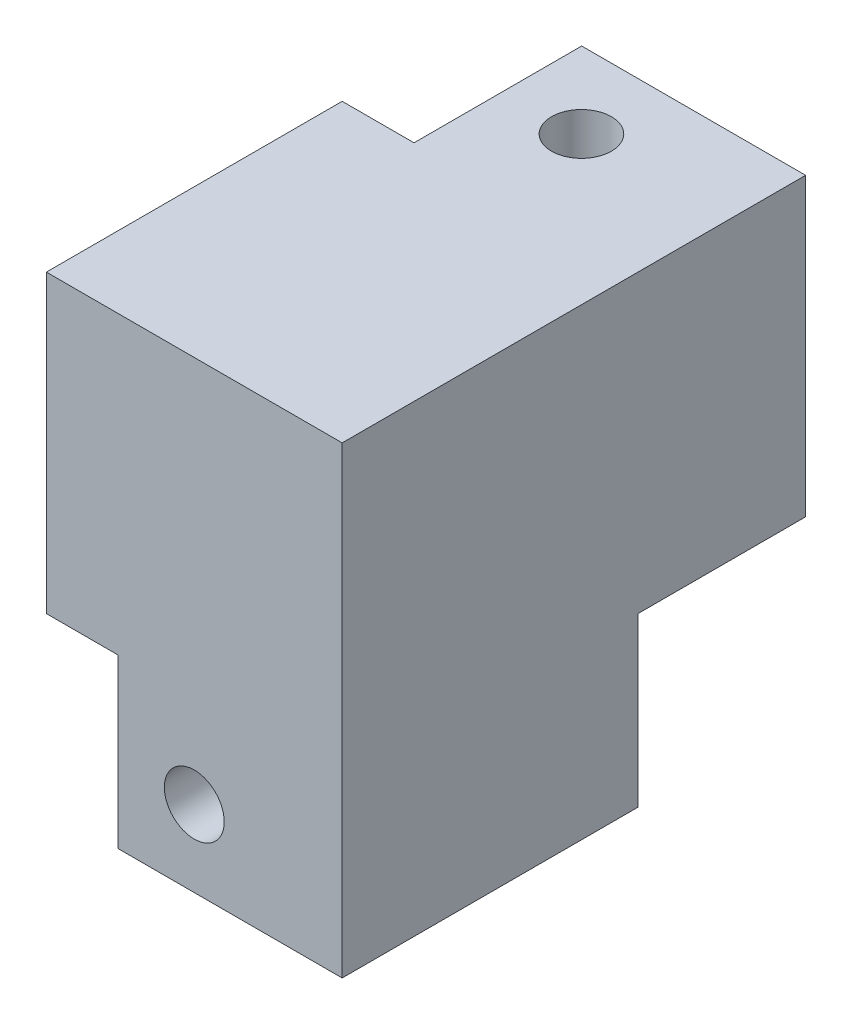
SolidWorks part; units mm, degrees
ref_plane "前视基准面" through (0, 0, 0) normal (0, 0, 1) x (1, 0, 0)
ref_plane "上视基准面" through (0, 0, 0) normal (0, 1, 0) x (1, 0, 0)
ref_plane "右视基准面" through (0, 0, 0) normal (1, 0, 0) x (0, 0, -1)
sketch "草图1" plane through (0, 0, 0) normal (0, 1, 0) x (1, 0, 0)
  line L1 (-6.35, -6.35) -> (6.35, -6.35)
  line L2 (-6.35, -6.35) -> (-6.35, 6.35)
  line L3 (-6.35, 6.35) -> (6.35, 6.35)
  line L4 (6.35, -6.35) -> (6.35, 6.35)
  line L5 (-6.35, -6.35) -> (6.35, 6.35) construction
  line L6 (-6.35, 6.35) -> (6.35, -6.35) construction
  line L7 (12.35, -12.35) -> (-12.35, -12.35)
  line L8 (12.35, -12.35) -> (12.35, 12.35)
  line L9 (12.35, 12.35) -> (-12.35, 12.35)
  line L10 (-12.35, -12.35) -> (-12.35, 12.35)
  line L11 (12.35, -12.35) -> (-12.35, 12.35) construction
  line L12 (12.35, 12.35) -> (-12.35, -12.35) construction
  point P0 (0, 0)
  point P6 (0, 0)
  dimension "D1" = 12.7
  dimension "D2" = 12.7
  dimension "D3" = 6
  dimension "D4" = 6
extrude "凸台-拉伸2" add sketch "草图1" along normal blind 24.7 contours L1 L4 L3 L2 | L10 L7 L8 L9 L4 L1 L2 L3
sketch "草图3" plane through (0, 0, 0) normal (0, -1, 0) x (1, 0, 0)
  line L0 (-6.35, 6.35) -> (-6.35, 12.35)
  line L1 (-6.35, -6.35) -> (6.35, -6.35)
  line L2 (-6.35, -6.35) -> (-6.35, 6.35)
  line L3 (-6.35, 6.35) -> (6.35, 6.35)
  line L4 (6.35, -6.35) -> (6.35, 6.35)
  line L5 (-6.35, -6.35) -> (6.35, 6.35) construction
  line L6 (-6.35, 6.35) -> (6.35, -6.35) construction
  line L7 (12.35, 12.35) -> (-12.35, 12.35) construction
  line L8 (-6.35, 12.35) -> (12.35, 12.35)
  line L9 (12.35, 12.35) -> (12.35, -12.35)
  line L10 (12.35, -12.35) -> (-6.35, -12.35)
  line L11 (12.35, -12.35) -> (-12.35, -12.35) construction
  line L12 (-6.35, -12.35) -> (-6.35, -6.35)
  point P0 (0, 0)
  line M4 (-12.35, -12.35) -> (12.35, -12.35)
  line M5 (12.35, -12.35) -> (12.35, 12.35)
  line M6 (12.35, 12.35) -> (-12.35, 12.35)
  dimension "D1" = 12.7
  dimension "D2" = 12.7
extrude "凸台-拉伸3" add sketch "草图3" along normal blind 14 contours L12 L0 L3 L4 L1 M4 M5 M6
sketch "草图4" plane through (0, 0, -12.35) normal (0, 0, -1) x (-1, 0, 0)
  line L0 (12.35, 24.7) -> (12.35, 0) construction
  line L1 (-6.35, 6) -> (6.35, 6)
  line L2 (-6.35, 6) -> (-6.35, 18.7)
  line L3 (-6.35, 18.7) -> (6.35, 18.7)
  line L4 (6.35, 6) -> (6.35, 18.7)
  line L5 (-6.35, 6) -> (6.35, 18.7) construction
  line L6 (-6.35, 18.7) -> (6.35, 6) construction
  line L7 (6.35, 18.7) -> (6.35, 24.7)
  line L8 (-12.35, 24.7) -> (12.35, 24.7) construction
  line L9 (6.35, 24.7) -> (-12.35, 24.7)
  line L10 (-12.35, 24.7) -> (-12.35, 0)
  line L11 (-12.35, 24.7) -> (-12.35, -14) construction
  line L12 (-12.35, 0) -> (6.35, 0)
  line L13 (6.35, 0) -> (6.35, 6)
  point P0 (0, 12.35)
  point P7 (12.35, 12.35)
  line M5 (-12.35, 24.7) -> (-12.35, -14)
  line M10 (12.35, 24.7) -> (-12.35, 24.7)
  dimension "D1" = 12.7
  dimension "D2" = 12.7
extrude "凸台-拉伸4" add sketch "草图4" along normal blind 14 contours L12 L13 L1 L2 L3 L7 M10 M5
sketch "草图5" plane through (0, 24.7, 0) normal (0, 1, 0) x (1, 0, 0)
  line L0 (-6.35, 12.35) -> (-12.35, 12.35) construction
  line L1 (-6.35, 26.35) -> (-6.35, 12.35) construction
  circle A0 centre (0, 19.98) radius 2.5
  dimension "D3" = 5
  dimension "D1" = 7.63
  dimension "D2" = 6.35
extrude "切除-拉伸1" cut sketch "草图5" against normal through all
sketch "草图6" plane through (0, 0, 12.35) normal (0, 0, 1) x (1, 0, 0)
  line L0 (-6.35, 0) -> (-12.35, 0) construction
  line L2 (-6.35, -14) -> (-6.35, 0) construction
  circle A0 centre (0, -7.63) radius 2.5
  point P6 (-6.35, -5.334)
  dimension "D3" = 5
  dimension "D1" = 7.63
  dimension "D2" = 6.35
extrude "切除-拉伸2" cut sketch "草图6" against normal through all
